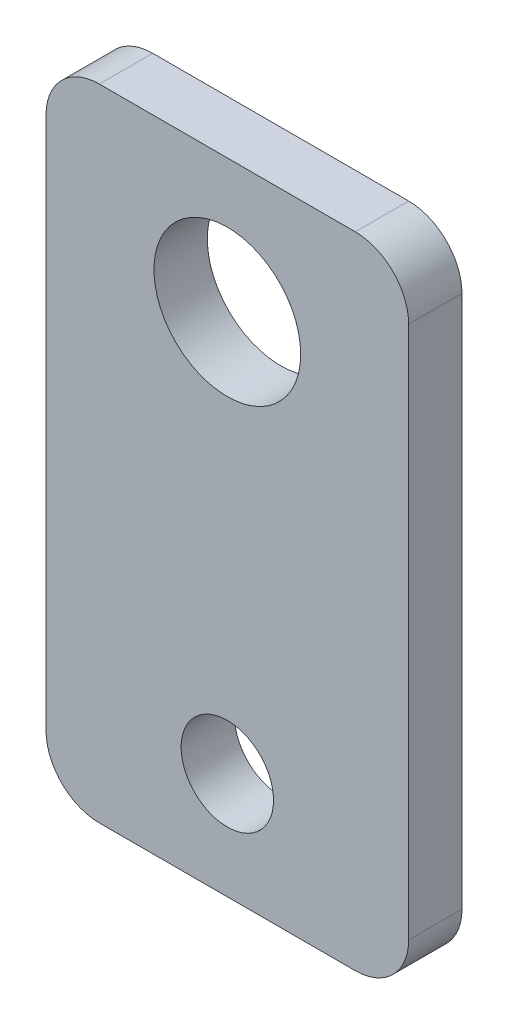
SolidWorks part; units mm, degrees
material "Custom Plastic"
ref_plane "X-Y Datum" through (0, 0, 0) normal (0, 0, 1) x (1, 0, 0)
ref_plane "X-Z Datum" through (0, 0, 0) normal (0, 1, 0) x (1, 0, 0)
ref_plane "Y-Z Datum" through (0, 0, 0) normal (1, 0, 0) x (0, 0, -1)
sketch "Sketch1" plane through (0, 0, 0) normal (0, 0, 1) x (1, 0, 0)
  line L1 (-10.795, 19.05) -> (10.795, 19.05)
  line L2 (-10.795, 19.05) -> (-10.795, -19.05)
  line L3 (-10.795, -19.05) -> (10.795, -19.05)
  line L4 (10.795, 19.05) -> (10.795, -19.05)
  line L5 (-10.795, 19.05) -> (10.795, -19.05) construction
  line L6 (-10.795, -19.05) -> (10.795, 19.05) construction
  circle A0 centre (0, 11.1125) radius 4.3688
  circle A1 centre (0, -12.7) radius 2.7508
  point P0 (0, 0)
  dimension "D3" = 5.5016
  dimension "D4" = 8.7376
  dimension "D1" = 38.1
  dimension "D2" = 21.59
  dimension "D5" = 7.9375
  dimension "D6" = 6.35
extrude "Boss-Extrude1" add sketch "Sketch1" along normal blind 3.175
fillet "Fillet1" radius 3.175 4 edges at (10.795, -19.05, 1.5875) (-10.795, -19.05, 1.5875) (-10.795, 19.05, 1.5875) (10.795, 19.05, 1.5875)
